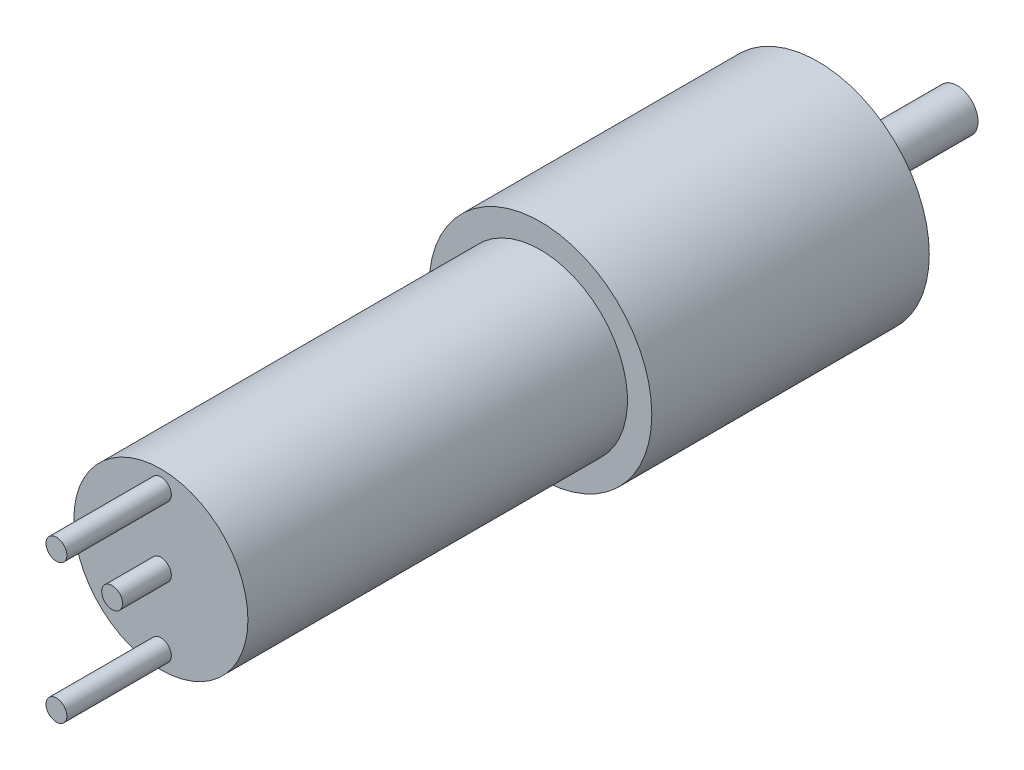
SolidWorks part; units mm, degrees
ref_plane "Plan de face" through (0, 0, 0) normal (0, 0, 1) x (1, 0, 0)
ref_plane "Plan de dessus" through (0, 0, 0) normal (0, 1, 0) x (1, 0, 0)
ref_plane "Plan de droite" through (0, 0, 0) normal (1, 0, 0) x (0, 0, -1)
sketch "Esquisse1" plane through (0, 0, 0) normal (0, 0, 1) x (1, 0, 0)
  circle A0 centre (0, 0) radius 12.5
extrude "Boss.-Extru.1" add sketch "Esquisse1" along normal blind 54.5
sketch "Esquisse2" plane through (0, 0, 54.5) normal (0, 0, 1) x (1, 0, 0)
  circle A0 centre (0, 0) radius 1.5
extrude "Boss.-Extru.2" add sketch "Esquisse2" along normal blind 7
sketch "Esquisse3" plane through (0, 0, 0) normal (0, 0, -1) x (-1, 0, 0)
  circle A0 centre (0, 0) radius 16
extrude "Boss.-Extru.3" add sketch "Esquisse3" along normal blind 39.85
sketch "Esquisse4" plane through (0, 0, -39.85) normal (0, 0, -1) x (-1, 0, 0)
  circle A0 centre (0, 0) radius 10
extrude "Boss.-Extru.4" add sketch "Esquisse4" along normal blind 3
sketch "Esquisse5" plane through (0, 0, -42.85) normal (0, 0, -1) x (-1, 0, 0)
  circle A0 centre (0, 0) radius 3
extrude "Boss.-Extru.5" add sketch "Esquisse5" along normal blind 17
sketch "Esquisse6" plane through (0, 0, 54.5) normal (0, 0, 1) x (1, 0, 0)
  circle A0 centre (0, 10) radius 1.5
  circle A1 centre (0, -10) radius 1.5
  circle A2 centre (0, 0) radius 1.5 construction
  dimension "D1" = 10
  dimension "D3" = 3
  dimension "D4" = 3
  dimension "D2" = 10
extrude "Boss.-Extru.6" add sketch "Esquisse6" along normal blind 15
